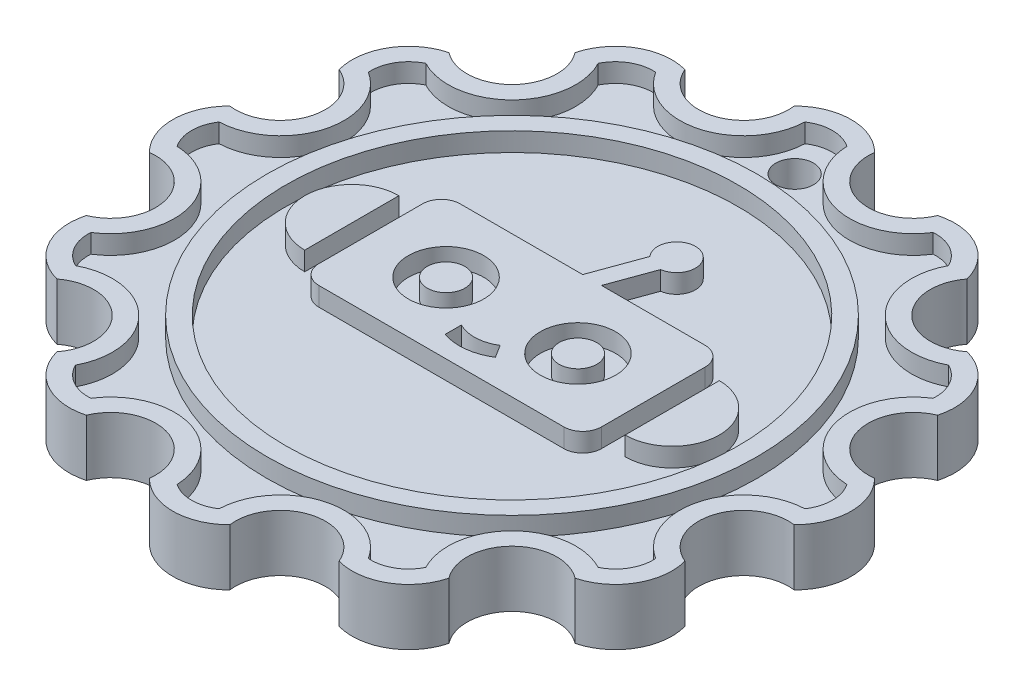
SolidWorks part; units mm, degrees
ref_plane "Front Plane" through (0, 0, 0) normal (0, 0, 1) x (1, 0, 0)
ref_plane "Top Plane" through (0, 0, 0) normal (0, 1, 0) x (1, 0, 0)
ref_plane "Right Plane" through (0, 0, 0) normal (1, 0, 0) x (0, 0, -1)
sketch "Sketch1" plane through (0, 0, 0) normal (0, 1, 0) x (1, 0, 0)
  arc A24 (31.7668, 13.4121) -> (34.2169, 4.2682) centre (33.5885, 9) ccw
  arc A25 (34.2169, -4.2682) -> (31.7668, -13.4121) centre (33.5885, -9) ccw
  arc A26 (27.4986, -20.8048) -> (20.8048, -27.4986) centre (24.5885, -24.5885) ccw
  arc A27 (13.4121, -31.7668) -> (4.2682, -34.2169) centre (9, -33.5885) ccw
  arc A28 (-4.2682, -34.2169) -> (-13.4121, -31.7668) centre (-9, -33.5885) ccw
  arc A29 (-20.8048, -27.4986) -> (-27.4986, -20.8048) centre (-24.5885, -24.5885) ccw
  arc A30 (-31.7668, -13.4121) -> (-34.2169, -4.2682) centre (-33.5885, -9) ccw
  arc A31 (-34.2169, 4.2682) -> (-31.7668, 13.4121) centre (-33.5885, 9) ccw
  arc A32 (-27.4986, 20.8048) -> (-20.8048, 27.4986) centre (-24.5885, 24.5885) ccw
  arc A33 (-13.4121, 31.7668) -> (-4.2682, 34.2169) centre (-9, 33.5885) ccw
  arc A34 (4.2682, 34.2169) -> (13.4121, 31.7668) centre (9, 33.5885) ccw
  arc A35 (20.8048, 27.4986) -> (27.4986, 20.8048) centre (24.5885, 24.5885) ccw
  arc A37 (-27.4986, 20.8048) -> (-31.7668, 13.4121) centre (-25.9808, 15) ccw
  arc A39 (-34.2169, 4.2682) -> (-34.2169, -4.2682) centre (-30, 0) ccw
  arc A41 (-31.7668, -13.4121) -> (-27.4986, -20.8048) centre (-25.9808, -15) ccw
  arc A43 (-20.8048, -27.4986) -> (-13.4121, -31.7668) centre (-15, -25.9808) ccw
  arc A44 (-4.2682, -34.2169) -> (4.2682, -34.2169) centre (0, -30) ccw
  arc A47 (13.4121, -31.7668) -> (20.8048, -27.4986) centre (15, -25.9808) ccw
  arc A48 (27.4986, -20.8048) -> (31.7668, -13.4121) centre (25.9808, -15) ccw
  arc A50 (34.2169, -4.2682) -> (34.2169, 4.2682) centre (30, 0) ccw
  arc A52 (31.7668, 13.4121) -> (27.4986, 20.8048) centre (25.9808, 15) ccw
  arc A54 (20.8048, 27.4986) -> (13.4121, 31.7668) centre (15, 25.9808) ccw
  arc A56 (4.2682, 34.2169) -> (-4.2682, 34.2169) centre (0, 30) ccw
  arc A58 (-13.4121, 31.7668) -> (-20.8048, 27.4986) centre (-15, 25.9808) ccw
  point P29 (0, 0)
  point P65 (0, 0)
  dimension "D2" = 12
extrude "Boss-Extrude1" add sketch "Sketch1" along normal blind 4
sketch "Sketch2" plane through (0, 4, 0) normal (0, 1, 0) x (1, 0, 0)
  circle A0 centre (0, 0) radius 26
  circle A1 centre (0, 0) radius 24
sketch "Sketch3" plane through (0, 4, 0) normal (0, 1, 0) x (1, 0, 0)
  arc A72 (-14.7267, 29.9714) -> (-18.5927, 27.7394) centre (-15, 25.9808) ccw
  arc A73 (-27.7394, 18.5927) -> (-18.5927, 27.7394) centre (-24.5885, 24.5885) ccw
  arc A74 (-27.7394, 18.5927) -> (-29.9714, 14.7267) centre (-25.9808, 15) ccw
  arc A75 (-33.3194, 2.232) -> (-29.9714, 14.7267) centre (-33.5885, 9) ccw
  arc A76 (-33.3194, 2.232) -> (-33.3194, -2.232) centre (-30, 0) ccw
  arc A77 (-29.9714, -14.7267) -> (-33.3194, -2.232) centre (-33.5885, -9) ccw
  arc A78 (-29.9714, -14.7267) -> (-27.7394, -18.5927) centre (-25.9808, -15) ccw
  arc A79 (-18.5927, -27.7394) -> (-27.7394, -18.5927) centre (-24.5885, -24.5885) ccw
  arc A80 (-18.5927, -27.7394) -> (-14.7267, -29.9714) centre (-15, -25.9808) ccw
  arc A81 (-2.232, -33.3194) -> (-14.7267, -29.9714) centre (-9, -33.5885) ccw
  arc A82 (-2.232, -33.3194) -> (2.232, -33.3194) centre (0, -30) ccw
  arc A83 (14.7267, -29.9714) -> (2.232, -33.3194) centre (9, -33.5885) ccw
  arc A84 (14.7267, -29.9714) -> (18.5927, -27.7394) centre (15, -25.9808) ccw
  arc A85 (27.7394, -18.5927) -> (18.5927, -27.7394) centre (24.5885, -24.5885) ccw
  arc A86 (27.7394, -18.5927) -> (29.9714, -14.7267) centre (25.9808, -15) ccw
  arc A87 (33.3194, -2.232) -> (29.9714, -14.7267) centre (33.5885, -9) ccw
  arc A88 (33.3194, -2.232) -> (33.3194, 2.232) centre (30, 0) ccw
  arc A89 (29.9714, 14.7267) -> (33.3194, 2.232) centre (33.5885, 9) ccw
  arc A90 (29.9714, 14.7267) -> (27.7394, 18.5927) centre (25.9808, 15) ccw
  arc A91 (18.5927, 27.7394) -> (27.7394, 18.5927) centre (24.5885, 24.5885) ccw
  arc A92 (18.5927, 27.7394) -> (14.7267, 29.9714) centre (15, 25.9808) ccw
  arc A93 (2.232, 33.3194) -> (14.7267, 29.9714) centre (9, 33.5885) ccw
  arc A94 (2.232, 33.3194) -> (-2.232, 33.3194) centre (0, 30) ccw
  arc A95 (-14.7267, 29.9714) -> (-2.232, 33.3194) centre (-9, 33.5885) ccw
  arc A96 (-14.7267, 29.9714) -> (-18.5927, 27.7394) centre (-15, 25.9808) ccw
  arc A97 (-27.7394, 18.5927) -> (-18.5927, 27.7394) centre (-24.5885, 24.5885) ccw
  arc A98 (-27.7394, 18.5927) -> (-29.9714, 14.7267) centre (-25.9808, 15) ccw
  arc A99 (-33.3194, 2.232) -> (-29.9714, 14.7267) centre (-33.5885, 9) ccw
  arc A100 (-33.3194, 2.232) -> (-33.3194, -2.232) centre (-30, 0) ccw
  arc A101 (-29.9714, -14.7267) -> (-33.3194, -2.232) centre (-33.5885, -9) ccw
  arc A102 (-29.9714, -14.7267) -> (-27.7394, -18.5927) centre (-25.9808, -15) ccw
  arc A103 (-18.5927, -27.7394) -> (-27.7394, -18.5927) centre (-24.5885, -24.5885) ccw
  arc A104 (-18.5927, -27.7394) -> (-14.7267, -29.9714) centre (-15, -25.9808) ccw
  arc A105 (-2.232, -33.3194) -> (-14.7267, -29.9714) centre (-9, -33.5885) ccw
  arc A106 (-2.232, -33.3194) -> (2.232, -33.3194) centre (0, -30) ccw
  arc A107 (14.7267, -29.9714) -> (2.232, -33.3194) centre (9, -33.5885) ccw
  arc A108 (14.7267, -29.9714) -> (18.5927, -27.7394) centre (15, -25.9808) ccw
  arc A109 (27.7394, -18.5927) -> (18.5927, -27.7394) centre (24.5885, -24.5885) ccw
  arc A110 (27.7394, -18.5927) -> (29.9714, -14.7267) centre (25.9808, -15) ccw
  arc A111 (33.3194, -2.232) -> (29.9714, -14.7267) centre (33.5885, -9) ccw
  arc A112 (33.3194, -2.232) -> (33.3194, 2.232) centre (30, 0) ccw
  arc A113 (29.9714, 14.7267) -> (33.3194, 2.232) centre (33.5885, 9) ccw
  arc A114 (29.9714, 14.7267) -> (27.7394, 18.5927) centre (25.9808, 15) ccw
  arc A115 (18.5927, 27.7394) -> (27.7394, 18.5927) centre (24.5885, 24.5885) ccw
  arc A116 (18.5927, 27.7394) -> (14.7267, 29.9714) centre (15, 25.9808) ccw
  arc A117 (2.232, 33.3194) -> (14.7267, 29.9714) centre (9, 33.5885) ccw
  arc A118 (2.232, 33.3194) -> (-2.232, 33.3194) centre (0, 30) ccw
  arc A119 (-14.7267, 29.9714) -> (-2.232, 33.3194) centre (-9, 33.5885) ccw
  dimension "D1" = 2
sketch "Sketch4" plane through (0, 4, 0) normal (0, 1, 0) x (1, 0, 0)
  arc A48 (-13.4121, 31.7668) -> (-20.8048, 27.4986) centre (-15, 25.9808) ccw
  arc A49 (-27.4986, 20.8048) -> (-20.8048, 27.4986) centre (-24.5885, 24.5885) ccw
  arc A50 (-27.4986, 20.8048) -> (-31.7668, 13.4121) centre (-25.9808, 15) ccw
  arc A51 (-34.2169, 4.2682) -> (-31.7668, 13.4121) centre (-33.5885, 9) ccw
  arc A52 (-34.2169, 4.2682) -> (-34.2169, -4.2682) centre (-30, 0) ccw
  arc A53 (-31.7668, -13.4121) -> (-34.2169, -4.2682) centre (-33.5885, -9) ccw
  arc A54 (-31.7668, -13.4121) -> (-27.4986, -20.8048) centre (-25.9808, -15) ccw
  arc A55 (-20.8048, -27.4986) -> (-27.4986, -20.8048) centre (-24.5885, -24.5885) ccw
  arc A56 (-20.8048, -27.4986) -> (-13.4121, -31.7668) centre (-15, -25.9808) ccw
  arc A57 (-4.2682, -34.2169) -> (-13.4121, -31.7668) centre (-9, -33.5885) ccw
  arc A58 (-4.2682, -34.2169) -> (4.2682, -34.2169) centre (0, -30) ccw
  arc A59 (13.4121, -31.7668) -> (4.2682, -34.2169) centre (9, -33.5885) ccw
  arc A60 (13.4121, -31.7668) -> (20.8048, -27.4986) centre (15, -25.9808) ccw
  arc A61 (27.4986, -20.8048) -> (20.8048, -27.4986) centre (24.5885, -24.5885) ccw
  arc A62 (27.4986, -20.8048) -> (31.7668, -13.4121) centre (25.9808, -15) ccw
  arc A63 (34.2169, -4.2682) -> (31.7668, -13.4121) centre (33.5885, -9) ccw
  arc A64 (34.2169, -4.2682) -> (34.2169, 4.2682) centre (30, 0) ccw
  arc A65 (31.7668, 13.4121) -> (34.2169, 4.2682) centre (33.5885, 9) ccw
  arc A66 (31.7668, 13.4121) -> (27.4986, 20.8048) centre (25.9808, 15) ccw
  arc A67 (20.8048, 27.4986) -> (27.4986, 20.8048) centre (24.5885, 24.5885) ccw
  arc A68 (20.8048, 27.4986) -> (13.4121, 31.7668) centre (15, 25.9808) ccw
  arc A69 (4.2682, 34.2169) -> (13.4121, 31.7668) centre (9, 33.5885) ccw
  arc A70 (4.2682, 34.2169) -> (-4.2682, 34.2169) centre (0, 30) ccw
  arc A71 (-13.4121, 31.7668) -> (-4.2682, 34.2169) centre (-9, 33.5885) ccw
  arc A72 (-13.4121, 31.7668) -> (-20.8048, 27.4986) centre (-15, 25.9808) ccw
  arc A73 (-27.4986, 20.8048) -> (-20.8048, 27.4986) centre (-24.5885, 24.5885) ccw
  arc A74 (-27.4986, 20.8048) -> (-31.7668, 13.4121) centre (-25.9808, 15) ccw
  arc A75 (-34.2169, 4.2682) -> (-31.7668, 13.4121) centre (-33.5885, 9) ccw
  arc A76 (-34.2169, 4.2682) -> (-34.2169, -4.2682) centre (-30, 0) ccw
  arc A77 (-31.7668, -13.4121) -> (-34.2169, -4.2682) centre (-33.5885, -9) ccw
  arc A78 (-31.7668, -13.4121) -> (-27.4986, -20.8048) centre (-25.9808, -15) ccw
  arc A79 (-20.8048, -27.4986) -> (-27.4986, -20.8048) centre (-24.5885, -24.5885) ccw
  arc A80 (-20.8048, -27.4986) -> (-13.4121, -31.7668) centre (-15, -25.9808) ccw
  arc A81 (-4.2682, -34.2169) -> (-13.4121, -31.7668) centre (-9, -33.5885) ccw
  arc A82 (-4.2682, -34.2169) -> (4.2682, -34.2169) centre (0, -30) ccw
  arc A83 (13.4121, -31.7668) -> (4.2682, -34.2169) centre (9, -33.5885) ccw
  arc A84 (13.4121, -31.7668) -> (20.8048, -27.4986) centre (15, -25.9808) ccw
  arc A85 (27.4986, -20.8048) -> (20.8048, -27.4986) centre (24.5885, -24.5885) ccw
  arc A86 (27.4986, -20.8048) -> (31.7668, -13.4121) centre (25.9808, -15) ccw
  arc A87 (34.2169, -4.2682) -> (31.7668, -13.4121) centre (33.5885, -9) ccw
  arc A88 (34.2169, -4.2682) -> (34.2169, 4.2682) centre (30, 0) ccw
  arc A89 (31.7668, 13.4121) -> (34.2169, 4.2682) centre (33.5885, 9) ccw
  arc A90 (31.7668, 13.4121) -> (27.4986, 20.8048) centre (25.9808, 15) ccw
  arc A91 (20.8048, 27.4986) -> (27.4986, 20.8048) centre (24.5885, 24.5885) ccw
  arc A92 (20.8048, 27.4986) -> (13.4121, 31.7668) centre (15, 25.9808) ccw
  arc A93 (4.2682, 34.2169) -> (13.4121, 31.7668) centre (9, 33.5885) ccw
  arc A94 (4.2682, 34.2169) -> (-4.2682, 34.2169) centre (0, 30) ccw
  arc A95 (-13.4121, 31.7668) -> (-4.2682, 34.2169) centre (-9, 33.5885) ccw
  dimension "D1" = 0
extrude "Boss-Extrude3" add sketch "Sketch4" along normal blind 2
extrude "Cut-Extrude1" cut sketch "Sketch3" along normal blind 2
extrude "Boss-Extrude4" add sketch "Sketch2" along normal blind 2
sketch "Sketch5" plane through (0, 4, 0) normal (0, 1, 0) x (1, 0, 0)
  line L0 (0, 7.5) -> (0, -7.5) construction
  line L1 (-15, -7.5) -> (15, -7.5)
  line L2 (-15, -7.5) -> (-15, 7.5)
  line L3 (-15, 7.5) -> (15, 7.5)
  line L4 (15, -7.5) -> (15, 7.5)
  line L5 (-15, -7.5) -> (15, 7.5) construction
  line L6 (-15, 7.5) -> (15, -7.5) construction
  line L7 (-17, 5) -> (-17, -5)
  line L8 (17, 5) -> (17, -5)
  arc A0 (-17, 5) -> (-17, -5) centre (-17, 0) ccw
  arc A1 (17, 5) -> (17, -5) centre (17, 0) cw
  circle A2 centre (-7, 0) radius 4
  circle A3 centre (-7, 0) radius 2
  circle A4 centre (7, 0) radius 2
  circle A5 centre (7, 0) radius 4
  point P0 (0, 0)
extrude "Boss-Extrude5" add sketch "Sketch5" along normal blind 2 contours L7 A0 | L1 L4 L3 L2 A2 A5 | A3 | A4 | A1 L8
sketch "Sketch6" plane through (0, 4, 0) normal (0, 1, 0) x (1, 0, 0)
  line L0 (0, 7.5) -> (1.9073, 12.7402)
  line L1 (-15, 7.5) -> (15, 7.5) construction
  line L2 (0, 7.5) -> (2, 7.5)
  line L4 (2, 7.5) -> (3.6733, 12.0974)
  arc A0 (3.6733, 12.0974) -> (1.9073, 12.7402) centre (3.3941, 14.0778) ccw
extrude "Boss-Extrude6" add sketch "Sketch6" along normal blind 2
sketch "Sketch7" plane through (0, 6, 0) normal (0, 1, 0) x (1, 0, 0)
  line L3 (2.1262, -3.3881) -> (2.5101, -4)
  line L4 (2.5101, -4) -> (2.9738, -4.7389)
  line L6 (-1.8, -3.5721) -> (-1.8, -5.2972)
  arc A0 (-1.8, -5.2972) -> (2.9738, -4.7389) centre (0, 0) ccw
  arc A1 (-1.8, -3.5721) -> (2.1262, -3.3881) centre (0, 0) ccw
extrude "Cut-Extrude2" cut sketch "Sketch7" against normal blind 2
sketch "Sketch8" plane through (0, 4, 0) normal (0, 1, 0) x (1, 0, 0)
  circle A1 centre (0, 30) radius 2
extrude "Cut-Extrude3" cut sketch "Sketch8" against normal blind 6
fillet "Fillet1" radius 2 4 edges at (15, 5, -7.5) (15, 5, 7.5) (-15, 5, 7.5) (-15, 5, -7.5)
